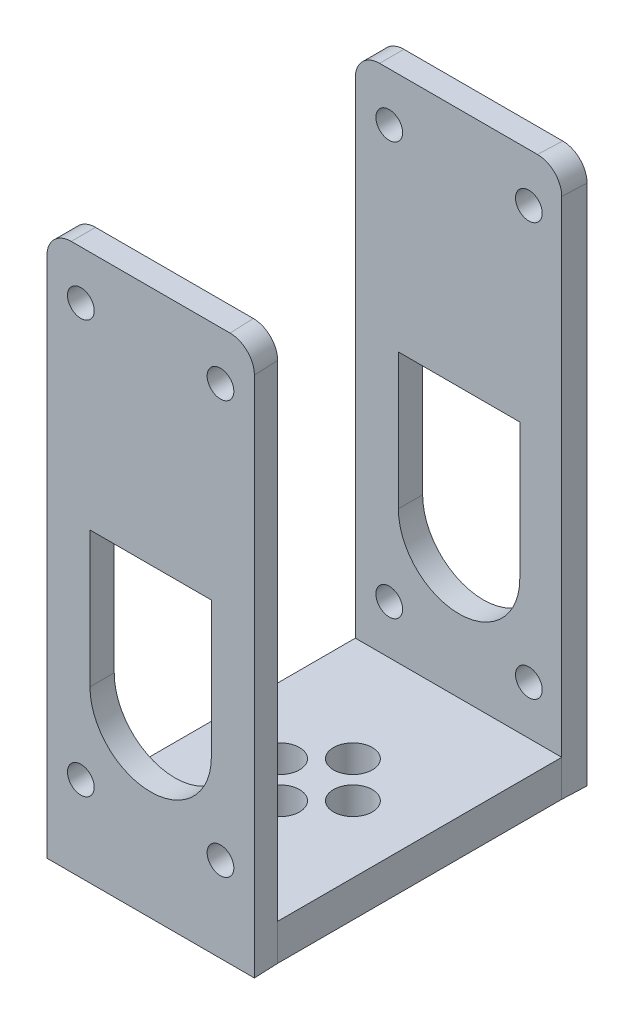
SolidWorks part; units mm, degrees
ref_plane "前视基准面" through (0, 0, 0) normal (0, 0, 1) x (1, 0, 0)
ref_plane "上视基准面" through (0, 0, 0) normal (0, 1, 0) x (1, 0, 0)
ref_plane "右视基准面" through (0, 0, 0) normal (1, 0, 0) x (0, 0, -1)
sketch "草图1" plane through (0, 0, 0) normal (0, 1, 0) x (1, 0, 0)
  line L0 (0, 0) -> (3.0259, 0) construction
  line L1 (-8.5, -11.7) -> (8.5, -11.7)
  line L2 (-8.5, -11.7) -> (-8.5, 11.7)
  line L3 (-8.5, 11.7) -> (8.5, 11.7)
  line L4 (8.5, -11.7) -> (8.5, 11.7)
  line L5 (-8.5, -11.7) -> (8.5, 11.7) construction
  line L6 (-8.5, 11.7) -> (8.5, -11.7) construction
  line L7 (0, 3) -> (0, 7.7277) construction
  circle A0 centre (0, 3) radius 1.6
  circle A1 centre (-3, 0) radius 1.6
  circle A2 centre (0, -3) radius 1.6
  circle A3 centre (3, 0) radius 1.6
  point P0 (0, 0)
  dimension "D3" = 3
  dimension "D1" = 23.4
  dimension "D2" = 17
  dimension "D4" = 3
extrude "凸台-拉伸1" add sketch "草图1" along normal blind 3
sketch "草图2" plane through (0, 0, 0) normal (0, -1, 0) x (1, 0, 0)
  line L0 (-8.5, 11.7) -> (-8.5, 13.7)
  line L1 (-8.5, 13.7) -> (8.584, 13.7)
  line L2 (8.584, 13.7) -> (8.5, 11.7)
  line L3 (8.5, 11.7) -> (-8.5, 11.7)
  line L4 (0, 0) -> (1.7925, 0) construction
  line L5 (8.584, -13.7) -> (8.5, -11.7)
  line L6 (-8.5, -13.7) -> (8.584, -13.7)
  line L7 (-8.5, -11.7) -> (-8.5, -13.7)
  line L8 (8.5, -11.7) -> (-8.5, -11.7)
  dimension "D1" = 2
extrude "凸台-拉伸3" add sketch "草图2" against normal blind 45
sketch "草图3" plane through (0, 0, 13.7) normal (0, 0, 1) x (1, 0, 0)
  line L0 (0.042, 0) -> (0.042, 7.7535) construction
  line L1 (8.584, 0) -> (-8.5, 0) construction
  line L2 (8.584, 45) -> (-8.5, 45) construction
  circle A0 centre (-5.708, 41) radius 1.1
  circle A1 centre (5.792, 41) radius 1.1
  circle A2 centre (0.042, 14) radius 5
  circle A3 centre (-5.708, 7) radius 1.1
  circle A4 centre (5.792, 7) radius 1.1
  dimension "D1" = 5.75
  dimension "D3" = 27
  dimension "D4" = 7
  dimension "D2" = 4
extrude "切除-拉伸1" cut sketch "草图3" against normal blind 45
fillet "圆角1" radius 2 4 edges at (8.542, 45, 12.7) (8.542, 45, -12.7) (-8.5, 45, 12.7) (-8.5, 45, -12.7)
sketch "草图4" plane through (0, 0, 13.7) normal (0, 0, 1) x (1, 0, 0)
  line L0 (-4.958, 14) -> (-4.958, 25.1878)
  line L1 (-4.958, 25.1878) -> (5.042, 25.1878)
  line L2 (5.042, 25.1878) -> (5.042, 14)
  line L3 (5.042, 14) -> (-4.958, 14)
  circle A0 centre (0.042, 14) radius 5 construction
extrude "切除-拉伸2" cut sketch "草图4" against normal blind 29
